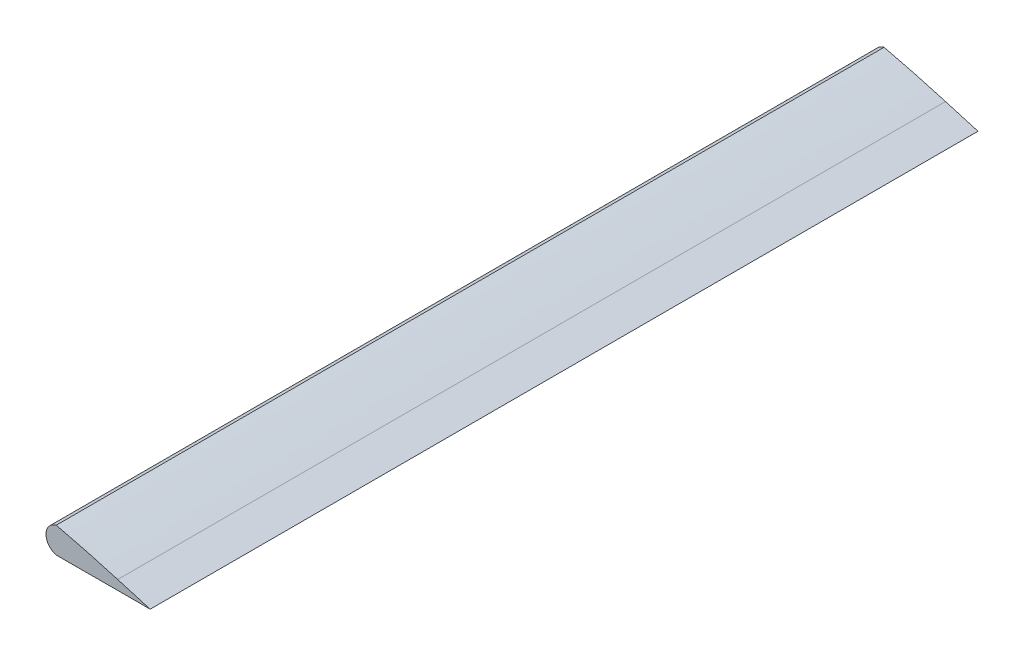
SolidWorks part; units mm, degrees
ref_plane "Front Plane" through (0, 0, 0) normal (0, 0, 1) x (1, 0, 0)
ref_plane "Top Plane" through (0, 0, 0) normal (0, 1, 0) x (1, 0, 0)
ref_plane "Right Plane" through (0, 0, 0) normal (1, 0, 0) x (0, 0, -1)
sketch "Sketch1" plane through (0, 0, 0) normal (0, 0, 1) x (1, 0, 0)
  line L6 (189.6983, 23.0776) -> (207.8496, 23.1125)
  line L7 (207.8496, 23.1125) -> (217.9653, 23.1125)
  line L8 (217.9653, 23.1125) -> (208.1997, 25.9631)
  arc A3 (189.6983, 30.8545) -> (189.6983, 23.0776) centre (190.6263, 26.9661) ccw
  spline S2 degree 2 poles (208.1997, 25.9631) (205.4612, 26.7625) (203.1725, 27.4044) (200.5088, 28.1515) (198.1271, 28.7776) (193.9496, 29.8758) (189.6983, 30.8545) knots 0 0 0 0.25 0.25 0.5 0.5 0.915467 0.915467 0.915467
extrude "Boss-Extrude1" add sketch "Sketch1" along normal blind 249
